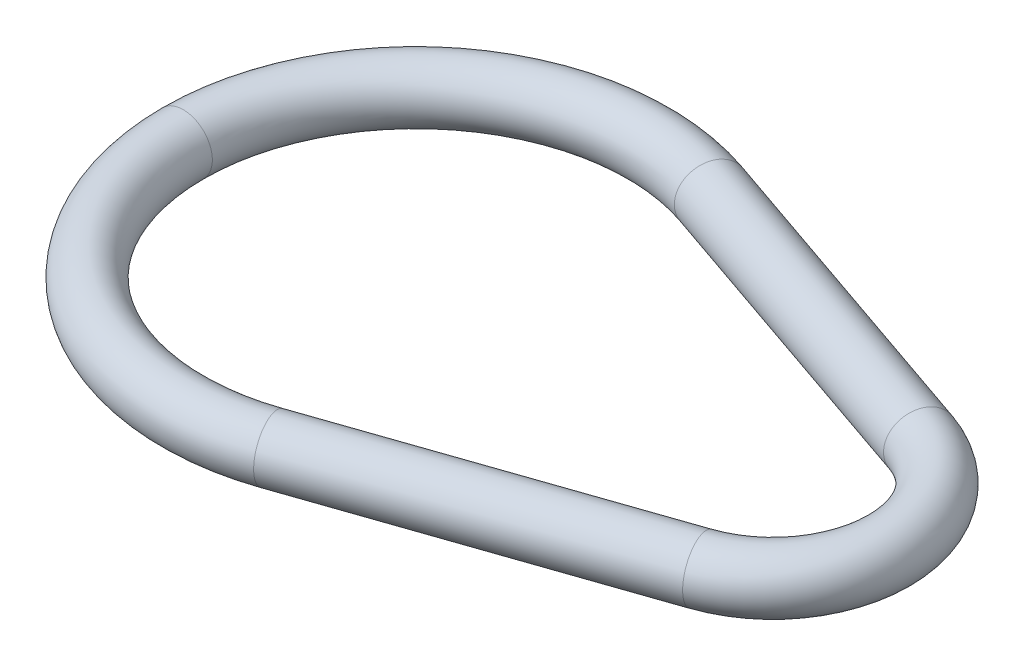
SolidWorks part; units mm, degrees
ref_plane "Front Plane" through (0, 0, 0) normal (0, 0, 1) x (1, 0, 0)
ref_plane "Top Plane" through (0, 0, 0) normal (0, 1, 0) x (1, 0, 0)
ref_plane "Right Plane" through (0, 0, 0) normal (1, 0, 0) x (0, 0, -1)
sketch "Sketch1" plane through (0, 0, 0) normal (0, 1, 0) x (1, 0, 0)
  line L0 (0, 0) -> (39, 0) construction
  line L1 (8.2713, 24.0155) -> (43.1356, 12.0078)
  line L2 (8.2713, -24.0155) -> (43.1356, -12.0078)
  arc A0 (43.1356, -12.0078) -> (43.1356, 12.0078) centre (39, 0) ccw
  arc A1 (8.2713, 24.0155) -> (8.2713, -24.0155) centre (0, 0) ccw
  dimension "D2" = 25.4
  dimension "D3" = 50.8
  dimension "D1" = 39
sketch "Sketch2" plane through (0, 0, 0) normal (0, 0, 1) x (1, 0, 0)
  line L0 (8.2713, 0) -> (-25.4, 0) construction
  line L1 (8.2713, 0) -> (-25.4, 0) construction
  circle A0 centre (-25.4, 0) radius 3.175
  dimension "D1" = 6.35
sweep "Sweep1" add profiles "Sketch2" path "Sketch1"
sketch "Sketch3" plane through (0, 0, 0) normal (0, 0, 1) x (1, 0, 0)
  line L0 (0, 0) -> (0, 27.8082) construction
  line L1 (0, 0) -> (39, 0) construction
  line L2 (39, 0) -> (39, 13.9041) construction
  dimension "D1" = 39
